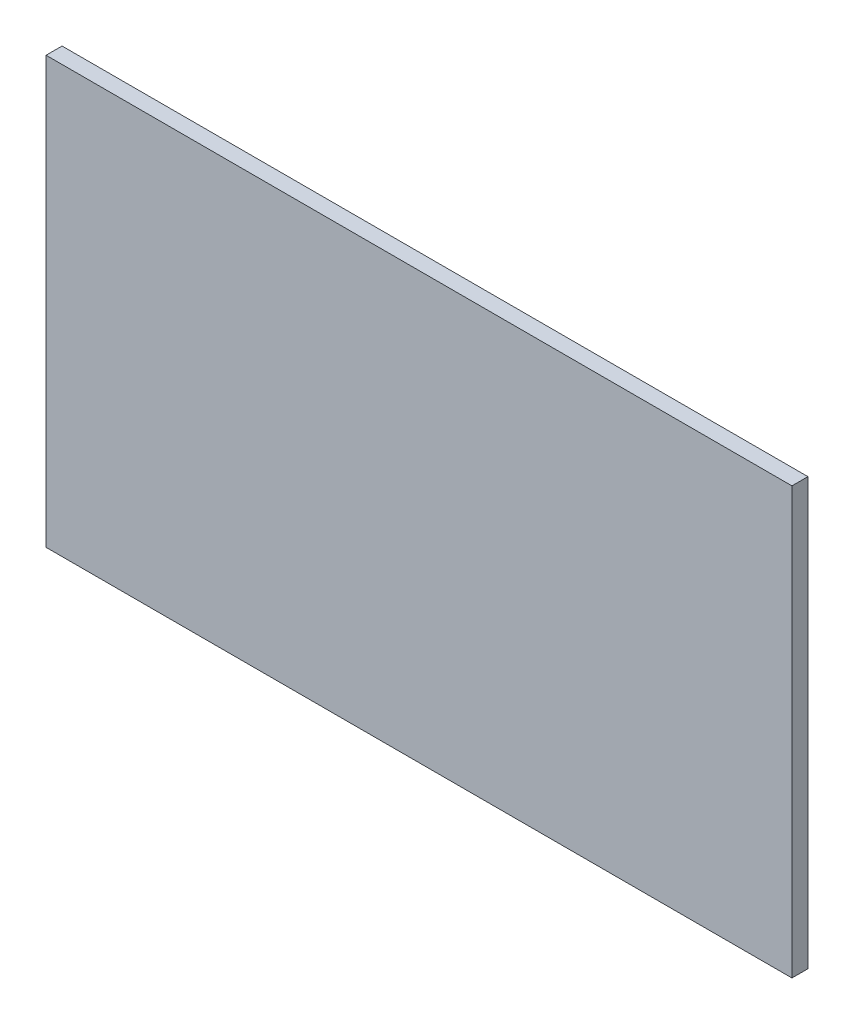
SolidWorks part; units mm, degrees
ref_plane "Front Plane" through (0, 0, 0) normal (0, 0, 1) x (1, 0, 0)
ref_plane "Top Plane" through (0, 0, 0) normal (0, 1, 0) x (1, 0, 0)
ref_plane "Right Plane" through (0, 0, 0) normal (1, 0, 0) x (0, 0, -1)
sketch "Sketch1" plane through (0, 0, 0) normal (0, 0, 1) x (1, 0, 0)
  line L1 (0, 0) -> (140, 0)
  line L2 (0, 0) -> (0, 80)
  line L3 (0, 80) -> (140, 80)
  line L4 (140, 0) -> (140, 80)
  dimension "D1" = 80
  dimension "D2" = 140
extrude "Boss-Extrude1" add sketch "Sketch1" along normal blind 3
